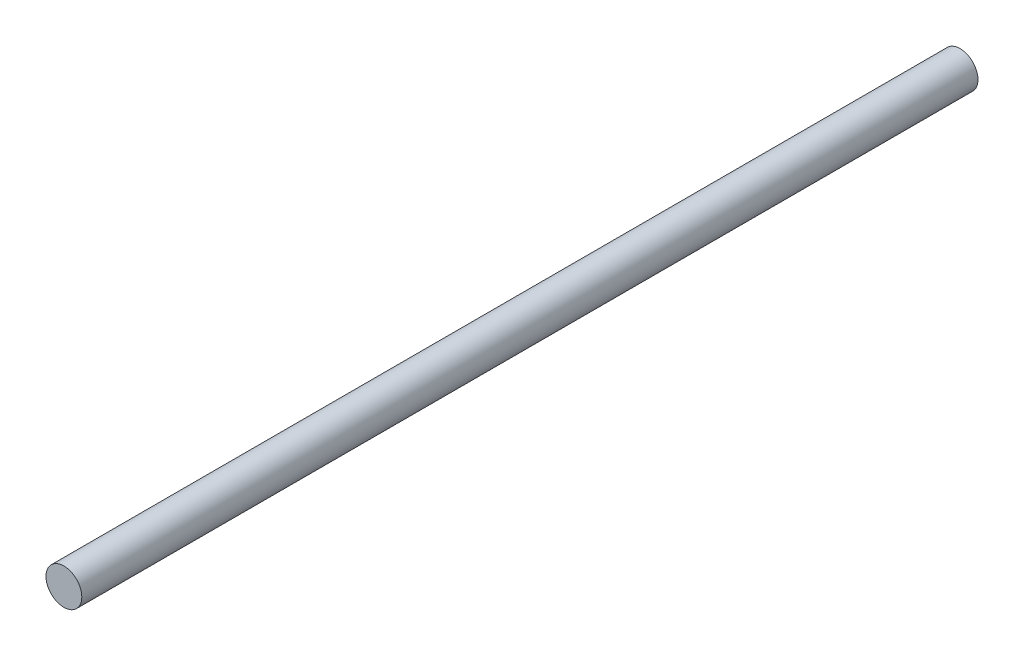
SolidWorks part; units mm, degrees
ref_plane "Plano frontal" through (0, 0, 0) normal (0, 0, 1) x (1, 0, 0)
ref_plane "Plano superior" through (0, 0, 0) normal (0, 1, 0) x (1, 0, 0)
ref_plane "Plano direito" through (0, 0, 0) normal (1, 0, 0) x (0, 0, -1)
sketch "Esboço1" plane through (0, 0, 25) normal (0, 0, 1) x (1, 0, 0)
  circle A0 centre (-24.6494, -15.5591) radius 2
  dimension "D1" = 4
extrude "Ressalto-extrusão1" add sketch "Esboço1" along normal blind 100
